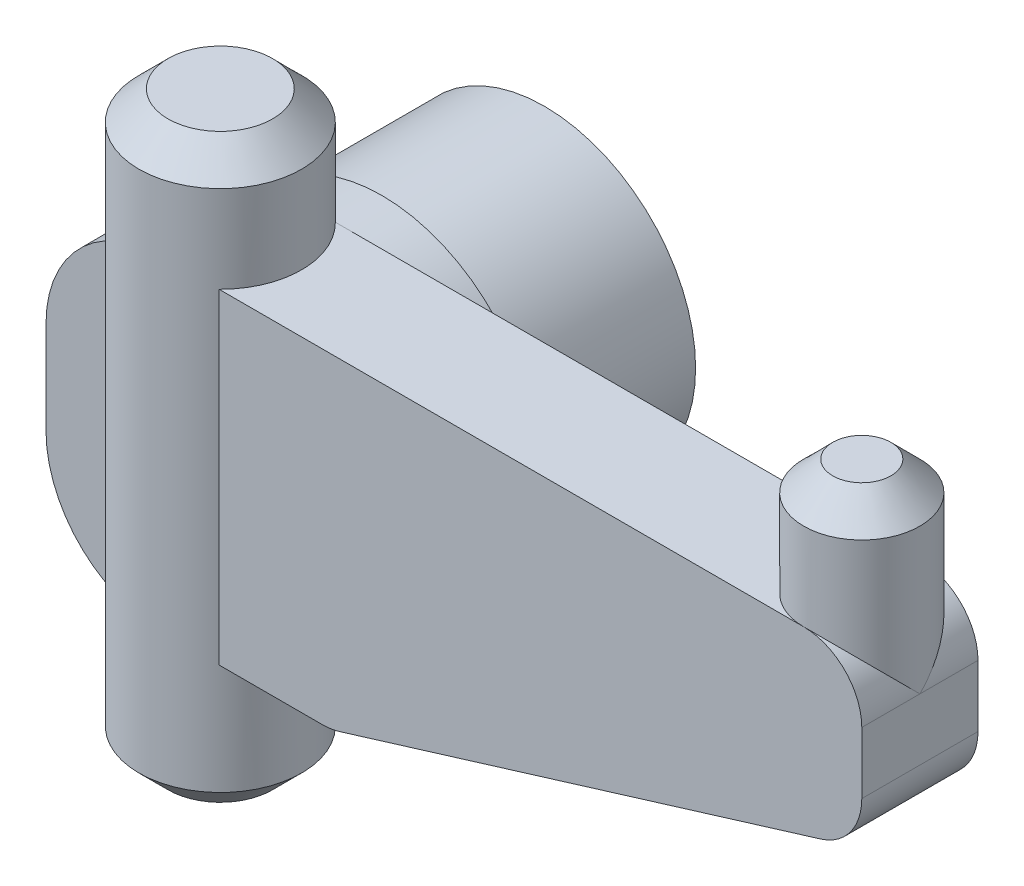
SolidWorks part; units mm, degrees
material "Alloy Steel (SS)"
ref_plane "Front Plane" through (0, 0, 0) normal (0, 0, 1) x (1, 0, 0)
ref_plane "Top Plane" through (0, 0, 0) normal (0, 1, 0) x (1, 0, 0)
ref_plane "Right Plane" through (0, 0, 0) normal (1, 0, 0) x (0, 0, -1)
sketch "Sketch1" plane through (0, 0, 0) normal (0, 0, 1) x (1, 0, 0)
  line L0 (-58.8182, 21.5635) -> (11.382, 21.5635)
  line L1 (11.382, 21.5635) -> (11.382, 7.5635)
  line L2 (-34.2829, -6.4365) -> (-58.8182, -6.4365)
  line L3 (-58.8182, -6.4365) -> (-58.8182, 21.5635)
  line L4 (-34.2829, -6.4365) -> (11.382, 7.5635)
extrude "Boss-Extrude1" add sketch "Sketch1" along normal blind 10
fillet "Fillet1" radius 10 2 edges at (-58.8182, -6.4365, 5) (-58.8182, 21.5635, 5)
fillet "Fillet2" radius 5 3 edges at (11.382, 21.5635, 5) (11.382, 7.5635, 5) (-34.2829, -6.4365, 5)
sketch "Sketch2" plane through (0, 21.5635, 0) normal (0, 1, 0) x (1, 0, 0)
  line L0 (-48.8182, 0) -> (-48.8182, -10) construction
  circle A0 centre (-48.8182, -5) radius 7
extrude "Boss-Extrude2" add sketch "Sketch2" along normal blind 10 and the other way blind 40
sketch "Sketch3" plane through (0, 21.5635, 0) normal (0, 1, 0) x (1, 0, 0)
  line L0 (6.382, -10) -> (6.382, 0) construction
  circle A0 centre (6.382, -5) radius 5
extrude "Boss-Extrude3" add sketch "Sketch3" along normal blind 10 and the other way up to vertex
chamfer "Chamfer1" distance 2.5 angle 45 3 edges at (-48.8182, -18.4365, 12) (6.382, 31.5635, 10) (-48.8182, 31.5635, 12)
sketch "Sketch4" plane through (0, 0, 0) normal (0, 0, -1) x (-1, 0, 0)
  line L0 (43.9192, -5.1543) -> (43.9192, 21.5635)
  arc A0 (53.7172, -5.1543) -> (58.8182, 3.5635) centre (48.8182, 3.5635) ccw construction
  circle A1 centre (43.9192, 8.2046) radius 13
extrude "Boss-Extrude4" add sketch "Sketch4" along normal blind 18 and the other way blind 10
sketch "Sketch5" plane through (0, 0, 0) normal (0, 0, -1) x (-1, 0, 0)
  circle A0 centre (43.9192, 8.2046) radius 13.3589
extrude "Boss-Extrude5" add sketch "Sketch5" along normal blind 4
